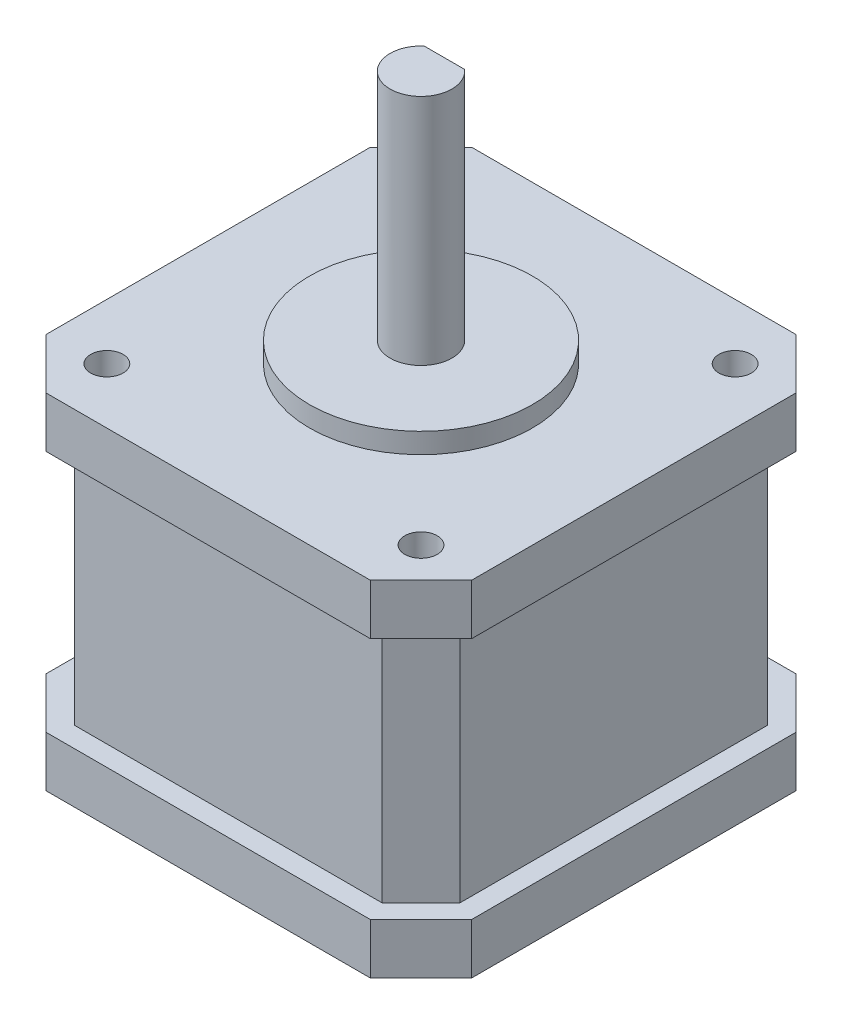
SolidWorks part; units mm, degrees
ref_plane "前视基准面" through (0, 0, 0) normal (0, 0, 1) x (1, 0, 0)
ref_plane "上视基准面" through (0, 0, 0) normal (0, 1, 0) x (1, 0, 0)
ref_plane "右视基准面" through (0, 0, 0) normal (1, 0, 0) x (0, 0, -1)
other "Configuration Table"
sketch "草图1" plane through (0, 0, 0) normal (0, 1, 0) x (1, 0, 0)
  line L1 (21, 21) -> (-21, 21)
  line L2 (21, 21) -> (21, -21)
  line L3 (21, -21) -> (-21, -21)
  line L4 (-21, 21) -> (-21, -21)
  line L5 (21, 21) -> (-21, -21) construction
  line L6 (21, -21) -> (-21, 21) construction
  point P0 (0, 0)
  dimension "D1" = 42
  dimension "D2" = 42
extrude "凸台-拉伸1" add sketch "草图1" along normal blind 34
sketch "草图2" plane through (0, 34, 0) normal (0, 1, 0) x (1, 0, 0)
  circle A0 centre (0, 0) radius 11
  dimension "D1" = 22
extrude "凸台-拉伸2" add sketch "草图2" along normal blind 2
sketch "草图3" plane through (0, 36, 0) normal (0, 1, 0) x (1, 0, 0)
  circle A0 centre (0, 0) radius 3.05
  dimension "D1" = 6.1
extrude "凸台-拉伸3" add sketch "草图3" along normal blind 23
sketch "草图4" plane through (0, 59, 0) normal (0, 1, 0) x (1, 0, 0)
  line L1 (-3.304, 5.0362) -> (3.2719, 5.0362)
  line L2 (-3.304, 5.0362) -> (-3.304, 2.3096)
  line L3 (-3.304, 2.3096) -> (3.2719, 2.3096)
  line L4 (3.2719, 5.0362) -> (3.2719, 2.3096)
extrude "切除-拉伸1" cut sketch "草图4" against normal blind 18
sketch "草图5" plane through (0, 34, 0) normal (0, 1, 0) x (1, 0, 0)
  line L1 (15.5, 15.5) -> (-15.5, 15.5)
  line L2 (15.5, 15.5) -> (15.5, -15.5)
  line L3 (15.5, -15.5) -> (-15.5, -15.5)
  line L4 (-15.5, 15.5) -> (-15.5, -15.5)
  line L5 (15.5, 15.5) -> (-15.5, -15.5) construction
  line L6 (15.5, -15.5) -> (-15.5, 15.5) construction
  circle A0 centre (15.5, 15.5) radius 1.6
  circle A1 centre (-15.5, 15.5) radius 1.6
  circle A2 centre (-15.5, -15.5) radius 1.6
  circle A3 centre (15.5, -15.5) radius 1.6
  point P0 (0, 0)
  dimension "D3" = 3.2
  dimension "D1" = 31
  dimension "D2" = 31
extrude "切除-拉伸2" cut sketch "草图5" against normal through all contours L3 A3 L2 | L2 A3 L3 | L3 A2 L4 | L1 A1 L4 | L4 A1 L1 | L1 A0 L2 | L2 A0 L1
chamfer "倒角1" distance 5 angle 45 4 edges at (21, 17, 21) (21, 17, -21) (-21, 17, -21) (-21, 17, 21)
ref_plane "基准面1" through (0, 5, 0) normal (0, -1, 0) x (-1, 0, 0)
sketch "草图6" plane through (0, 5, 0) normal (0, -1, 0) x (-1, 0, 0)
  line L12 (-21, 16) -> (-21, -16)
  line L13 (-21, -16) -> (-16, -21)
  line L14 (-16, -21) -> (16, -21)
  line L15 (16, -21) -> (21, -16)
  line L16 (21, -16) -> (21, 16)
  line L17 (21, 16) -> (16, 21)
  line L18 (16, 21) -> (-16, 21)
  line L19 (-16, 21) -> (-21, 16)
  line L20 (-21, 16) -> (-21, -16)
  line L21 (-21, -16) -> (-16, -21)
  line L22 (-16, -21) -> (16, -21)
  line L23 (16, -21) -> (21, -16)
  line L24 (21, -16) -> (21, 16)
  line L25 (21, 16) -> (16, 21)
  line L26 (16, 21) -> (-16, 21)
  line L27 (-16, 21) -> (-21, 16)
  line L36 (-19, 15.1716) -> (-19, -15.1716)
  line L37 (-19, -15.1716) -> (-15.1716, -19)
  line L38 (-15.1716, -19) -> (15.1716, -19)
  line L39 (15.1716, -19) -> (19, -15.1716)
  line L40 (19, -15.1716) -> (19, 15.1716)
  line L41 (19, 15.1716) -> (15.1716, 19)
  line L42 (15.1716, 19) -> (-15.1716, 19)
  line L43 (-15.1716, 19) -> (-19, 15.1716)
  line L44 (-19, 15.1716) -> (-19, -15.1716)
  line L45 (-19, -15.1716) -> (-15.1716, -19)
  line L46 (-15.1716, -19) -> (15.1716, -19)
  line L47 (15.1716, -19) -> (19, -15.1716)
  line L48 (19, -15.1716) -> (19, 15.1716)
  line L49 (19, 15.1716) -> (15.1716, 19)
  line L50 (15.1716, 19) -> (-15.1716, 19)
  line L51 (-15.1716, 19) -> (-19, 15.1716)
  dimension "D1" = 0
  dimension "D2" = 2
extrude "切除-拉伸3" cut sketch "草图6" against normal blind 24
sketch "草图7" plane through (0, 0, -21) normal (0, 0, -1) x (-1, 0, 0)
  line L0 (-16, 0) -> (16, 0) construction
  line L1 (-6, 0) -> (6, 0)
  line L2 (-6, 0) -> (-6, 5)
  line L3 (-6, 5) -> (6, 5)
  line L4 (6, 0) -> (6, 5)
  line L5 (15.1716, 5) -> (-15.1716, 5) construction
  dimension "D1" = 6
  dimension "D2" = 12
extrude "凸台-拉伸4" add sketch "草图7" along normal blind 5
sketch "草图8" plane through (0, 0, -26) normal (0, 0, -1) x (-1, 0, 0)
  line L0 (15.1716, 5) -> (-15.1716, 5) construction
  line L1 (-4.7888, 5) -> (4.9841, 5)
  line L2 (-4.7888, 5) -> (-4.7888, 1.307)
  line L3 (-4.7888, 1.307) -> (4.9841, 1.307)
  line L4 (4.9841, 5) -> (4.9841, 1.307)
extrude "切除-拉伸4" cut sketch "草图8" against normal blind 4
